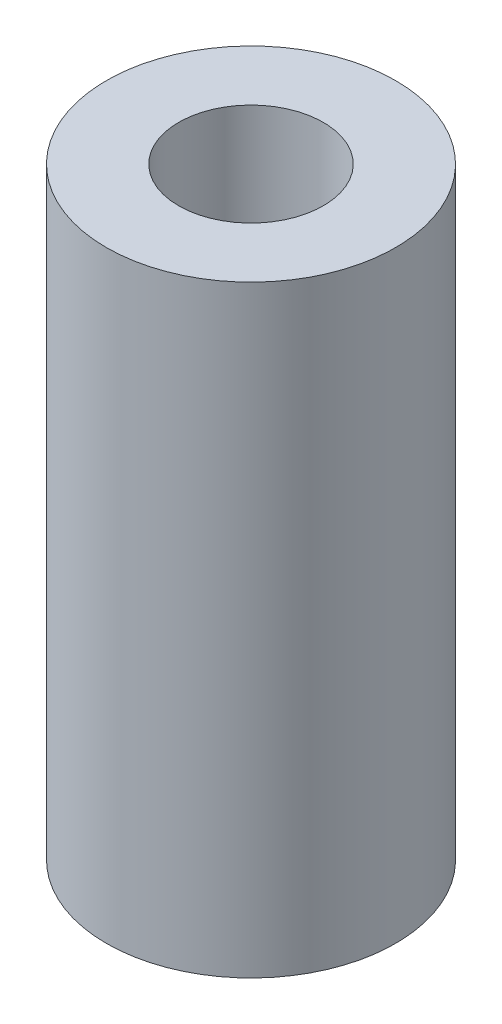
SolidWorks part; units mm, degrees
material "Nylon 6/10"
ref_plane "Front Plane" through (0, 0, 0) normal (0, 0, 1) x (1, 0, 0)
ref_plane "Top Plane" through (0, 0, 0) normal (0, 1, 0) x (1, 0, 0)
ref_plane "Right Plane" through (0, 0, 0) normal (1, 0, 0) x (0, 0, -1)
sketch "Sketch1" plane through (0, 0, 0) normal (0, 1, 0) x (1, 0, 0)
  circle A0 centre (0, 0) radius 3
  circle A1 centre (0, 0) radius 1.5
  dimension "D1" = 3
  dimension "D2" = 6
extrude "Extrude1" add sketch "Sketch1" along normal blind 12.5
